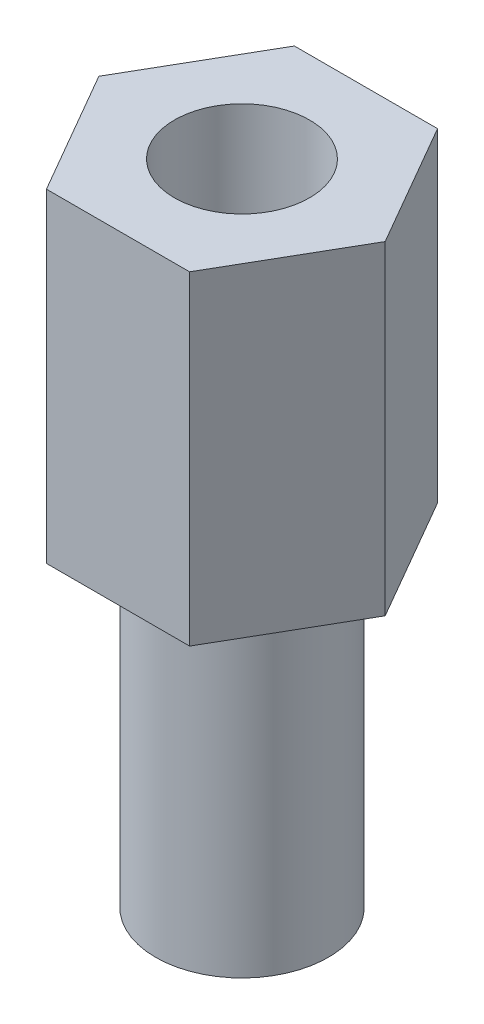
SolidWorks part; units mm, degrees
ref_plane "前视基准面" through (0, 0, 0) normal (0, 0, 1) x (1, 0, 0)
ref_plane "上视基准面" through (0, 0, 0) normal (0, 1, 0) x (1, 0, 0)
ref_plane "右视基准面" through (0, 0, 0) normal (1, 0, 0) x (0, 0, -1)
sketch "草图4" plane through (0, 0, 0) normal (0, 1, 0) x (1, 0, 0)
  line L0 (-12.7945, 0) -> (16.3015, 0) construction
  line L2 (1.325, -2.295) -> (2.65, 0)
  line L3 (2.65, 0) -> (1.325, 2.295)
  line L4 (1.325, 2.295) -> (-1.325, 2.295)
  line L5 (-1.325, 2.295) -> (-2.65, 0)
  line L6 (-2.65, 0) -> (-1.325, -2.295)
  line L7 (-1.325, -2.295) -> (1.325, -2.295)
  circle A0 centre (0, 0) radius 2.295 construction
  dimension "D1" = 5.3
extrude "凸台-拉伸1" add sketch "草图4" along normal blind 6
sketch "草图6" plane through (0, 0, 0) normal (0, -1, 0) x (-1, 0, 0)
  circle A0 centre (0, 0) radius 1.6
  dimension "D1" = 3.2
extrude "凸台-拉伸2" add sketch "草图6" along normal blind 6
cosmetic thread "装饰螺纹线1" parameters "D2"=2.5
sketch "草图7" plane through (0, 6, 0) normal (0, 1, 0) x (1, 0, 0)
  circle A0 centre (0, 0) radius 1.25
  dimension "D1" = 2.5
extrude "切除-拉伸1" cut sketch "草图7" against normal blind 5
cosmetic thread "装饰螺纹线2" parameters "D2"=3
